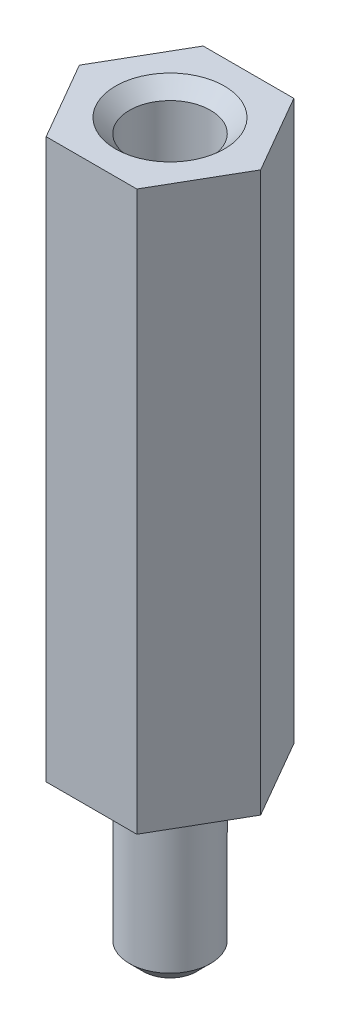
SolidWorks part; units mm, degrees
ref_plane "Front Plane" through (0, 0, 0) normal (0, 0, 1) x (1, 0, 0)
ref_plane "Top Plane" through (0, 0, 0) normal (0, 1, 0) x (1, 0, 0)
ref_plane "Right Plane" through (0, 0, 0) normal (1, 0, 0) x (0, 0, -1)
ref_plane "Plane1" through (0, 20, 0) normal (0, 1, 0) x (1, 0, 0)
sketch "Sketch1" plane through (0, 20, 0) normal (0, 1, 0) x (1, 0, 0)
  line L0 (1.6224, -2.81) -> (3.2447, 0)
  line L1 (3.2447, 0) -> (1.6224, 2.81)
  line L2 (1.6224, 2.81) -> (-1.6224, 2.81)
  line L3 (-1.6224, 2.81) -> (-3.2447, 0)
  line L4 (-3.2447, 0) -> (-1.6224, -2.81)
  line L5 (-1.6224, -2.81) -> (1.6224, -2.81)
extrude "Boss-Extrude1" add sketch "Sketch1" against normal blind 20
ref_plane "Plane2" through (0, 0, 0) normal (0, 0, -1) x (-1, 0, 0)
sketch "Sketch2" plane through (0, 0, 0) normal (0, 0, -1) x (-1, 0, 0)
  line L0 (-1.45, -6) -> (0, -6)
  line L1 (0, -6) -> (0, 0)
  line L2 (0, 0) -> (-1.45, 0)
  line L3 (-1.45, 0) -> (-1.45, -6)
  line L4 (0, -6) -> (0, 0) construction
revolve "Revolve1" add sketch "Sketch2" angle 360 about L4
hole_wizard "Ø2.9 (2.9) Diameter Hole1" positions "Sketch4" profile "Sketch3" hole size "Ø2.9" standard "ANSI Metric"
sketch "Sketch4" plane through (0, 20, 0) normal (0, 1, 0) x (1, 0, 0)
  point P0 (0, 0)
sketch "Sketch3" plane through (0, 20, 0) normal (1, 0, 0) x (0, 0, 1)
  line L0 (0, 0) -> (0, 5)
  line L1 (0, 5) -> (1.45, 5)
  line L2 (1.45, 5) -> (1.45, 0)
  line L5 (1.45, 0) -> (0, 0)
  line L10 (0, 5) -> (-1.45, 5) construction
  line L11 (0, -6.35) -> (0, 107.95) construction
  dimension "Hole Dia." = 2.9
  dimension "Hole Depth" = 5
  dimension "Drill Angle" = 180
chamfer "Chamfer1" distance 0.5 angle 45 2 edges at (0, -6, 1.45) (0, 20, 1.45)
